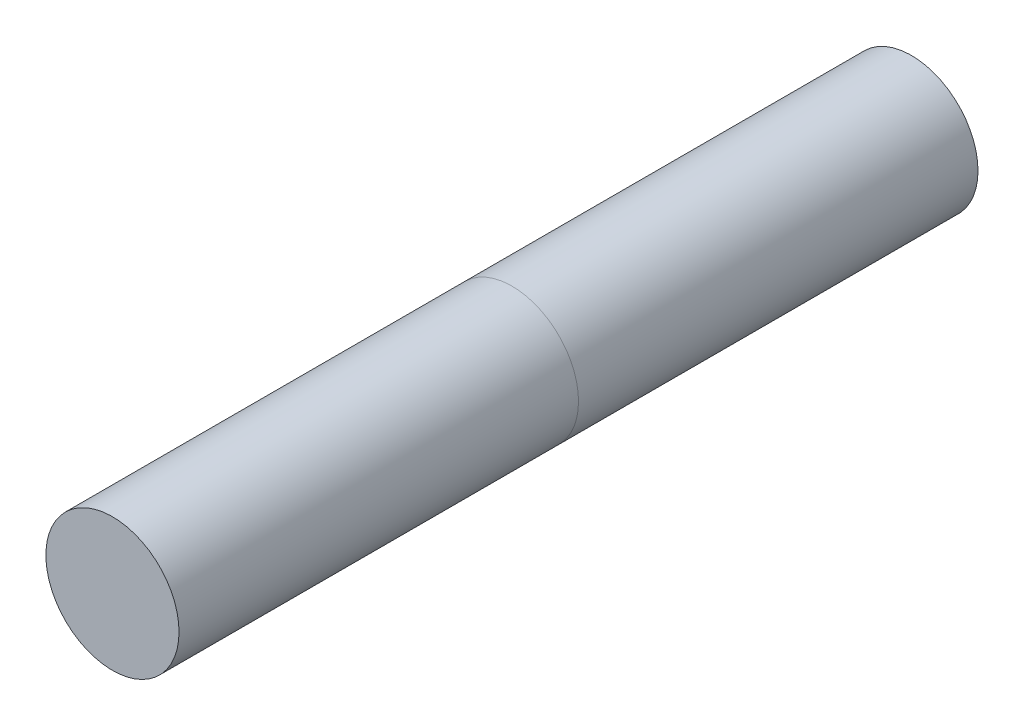
SolidWorks part; units mm, degrees
ref_plane "Front Plane" through (0, 0, 0) normal (0, 0, 1) x (1, 0, 0)
ref_plane "Top Plane" through (0, 0, 0) normal (0, 1, 0) x (1, 0, 0)
ref_plane "Right Plane" through (0, 0, 0) normal (1, 0, 0) x (0, 0, -1)
sketch "Sketch1" plane through (0, 0, 0) normal (0, 0, 1) x (1, 0, 0)
  circle A0 centre (0, 0) radius 2.5
  dimension "D1" = 5
extrude "Boss-Extrude1" add sketch "Sketch1" along normal blind 15
sketch "Sketch2" plane through (0, 0, 15) normal (0, 0, 1) x (1, 0, 0)
  circle A0 centre (0, 0) radius 2.5
extrude "Boss-Extrude2" add sketch "Sketch2" along normal blind 15 separate body
